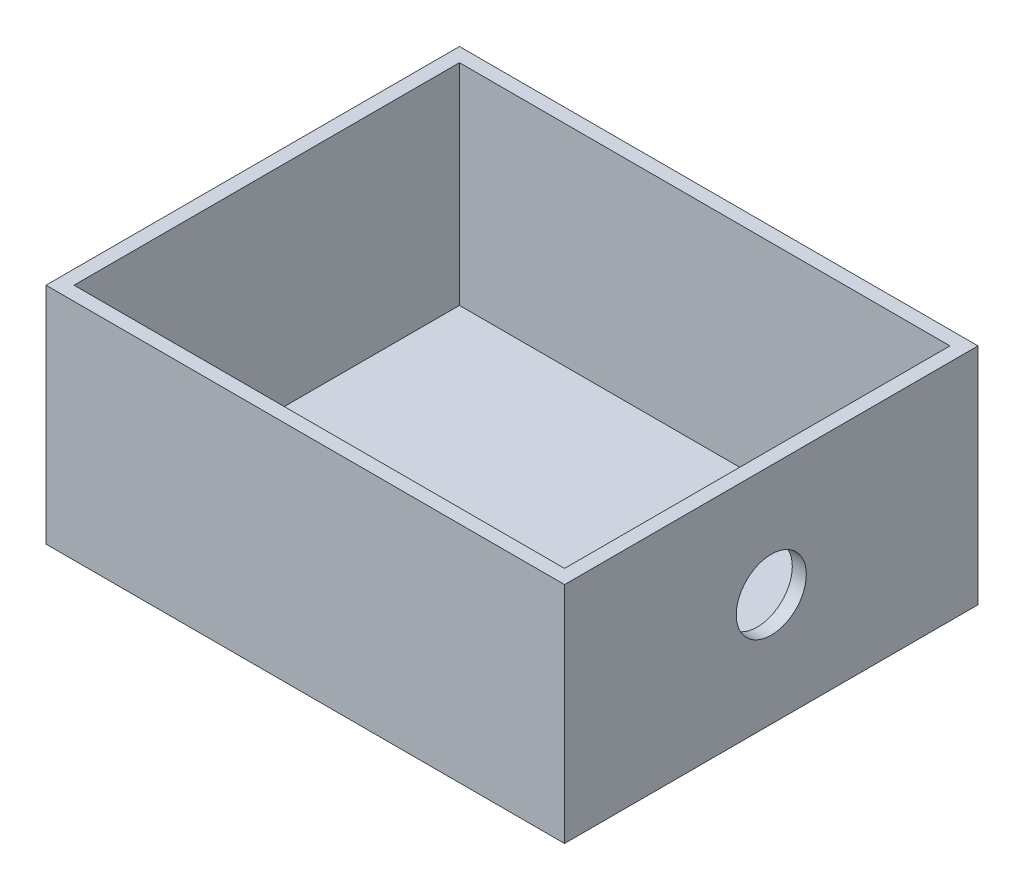
SolidWorks part; units mm, degrees
ref_plane "Front Plane" through (0, 0, 0) normal (0, 0, 1) x (1, 0, 0)
ref_plane "Top Plane" through (0, 0, 0) normal (0, 1, 0) x (1, 0, 0)
ref_plane "Right Plane" through (0, 0, 0) normal (1, 0, 0) x (0, 0, -1)
sketch "Sketch1" plane through (0, 0, 0) normal (0, 1, 0) x (1, 0, 0)
  line L1 (-37, -29.5) -> (37, -29.5)
  line L2 (-37, -29.5) -> (-37, 29.5)
  line L3 (-37, 29.5) -> (37, 29.5)
  line L4 (37, -29.5) -> (37, 29.5)
  line L5 (-37, -29.5) -> (37, 29.5) construction
  line L6 (-37, 29.5) -> (37, -29.5) construction
  point P0 (0, 0)
  dimension "D1" = 74
  dimension "D2" = 59
extrude "Boss-Extrude1" add sketch "Sketch1" along normal blind 32
shell "Shell1" thickness 2
sketch "Sketch2" plane through (37, 0, 0) normal (1, 0, 0) x (0, 0, -1)
  line L0 (-29.5, 0) -> (29.5, 0) construction
  line L1 (-29.5, 32) -> (-29.5, 0) construction
  circle A0 centre (0, 16) radius 5
  dimension "D1" = 10
  dimension "D2" = 16
  dimension "D3" = 29.5
extrude "Cut-Extrude1" cut sketch "Sketch2" against normal blind 3
